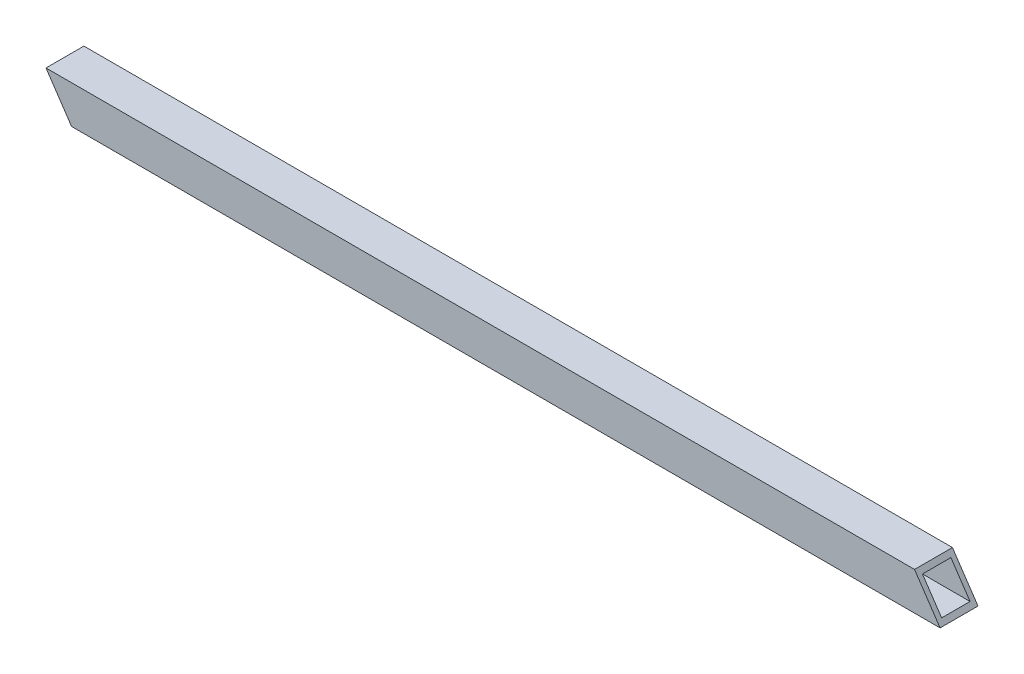
SolidWorks part; units mm, degrees
material "AISI 1020"
ref_plane "Front Plane" through (0, 0, 0) normal (0, 0, 1) x (1, 0, 0)
ref_plane "Top Plane" through (0, 0, 0) normal (0, 1, 0) x (1, 0, 0)
ref_plane "Right Plane" through (0, 0, 0) normal (1, 0, 0) x (0, 0, -1)
sketch "Sketch2" plane through (0, 0, 0) normal (1, 0, 0) x (0, 0, -1)
  line L1 (197.6047, 470.8123) -> (235.7047, 470.8123)
  line L2 (197.6047, 470.8123) -> (197.6047, 432.7123)
  line L3 (197.6047, 432.7123) -> (235.7047, 432.7123)
  line L4 (235.7047, 470.8123) -> (235.7047, 432.7123)
  line L5 (197.6047, 470.8123) -> (235.7047, 432.7123) construction
  line L6 (197.6047, 432.7123) -> (235.7047, 470.8123) construction
  line L7 (242.0547, 426.3623) -> (191.2547, 426.3623)
  line L8 (242.0547, 426.3623) -> (242.0547, 477.1623)
  line L9 (242.0547, 477.1623) -> (191.2547, 477.1623)
  line L10 (191.2547, 426.3623) -> (191.2547, 477.1623)
  line L11 (242.0547, 426.3623) -> (191.2547, 477.1623) construction
  line L12 (242.0547, 477.1623) -> (191.2547, 426.3623) construction
  point P0 (216.6547, 451.7623)
  point P5 (216.6547, 451.7623)
  dimension "D1" = 6.35
  dimension "D2" = 6.35
  dimension "D3" = 50.8
  dimension "D4" = 50.8
extrude "Boss-Extrude1" add sketch "Sketch2" along normal blind 1930.4 contours L9 L10 L7 L8
sketch "Sketch4" plane through (0, 0, 0) normal (-1, 0, 0) x (0, 0, 1)
  line L0 (-191.2547, 426.3623) -> (-191.2547, 477.1623) construction
  line L1 (-235.7047, 432.7123) -> (-197.6047, 432.7123)
  line L2 (-235.7047, 432.7123) -> (-235.7047, 470.8123)
  line L3 (-235.7047, 470.8123) -> (-197.6047, 470.8123)
  line L4 (-197.6047, 432.7123) -> (-197.6047, 470.8123)
  line L5 (-235.7047, 432.7123) -> (-197.6047, 470.8123) construction
  line L6 (-235.7047, 470.8123) -> (-197.6047, 432.7123) construction
  line L7 (-242.0547, 426.3623) -> (-242.0547, 477.1623) construction
  line L8 (-242.0547, 477.1623) -> (-191.2547, 477.1623) construction
  line L9 (-242.0547, 426.3623) -> (-191.2547, 426.3623) construction
  point P0 (-216.6547, 451.7623)
  dimension "D1" = 6.35
  dimension "D2" = 6.35
  dimension "D3" = 6.35
  dimension "D4" = 6.35
extrude "Cut-Extrude1" cut sketch "Sketch4" against normal through all
sketch "Sketch5" plane through (0, 0, -191.2547) normal (0, 0, 1) x (1, 0, 0)
  line L0 (0, 477.1623) -> (34.265, 426.3623)
  line L1 (34.265, 426.3623) -> (0, 426.3623)
  line L2 (0, 426.3623) -> (0, 477.1623)
  line L3 (1930.4, 426.3623) -> (0, 426.3623) construction
  line L4 (1164.2416, 477.1623) -> (1930.4, -658.7143)
  line L5 (1930.4, 477.1623) -> (0, 477.1623) construction
  line L6 (1930.4, -658.7143) -> (1930.4, 477.1623)
  line L7 (1930.4, 477.1623) -> (1164.2416, 477.1623)
  line L8 (1930.4, 426.3623) -> (1930.4, 477.1623) construction
  dimension "D1" = 56
  dimension "D2" = 965.2
extrude "Cut-Extrude2" cut sketch "Sketch5" against normal through all
equation "\"D1@Boss-Extrude1\"=\"Length@Default@Extruded 2x2x.25.SLDPRT\"*2"
equation "\"D2@Sketch5\"=\"Length@Default@Extruded 2x2x.25.SLDPRT\""
